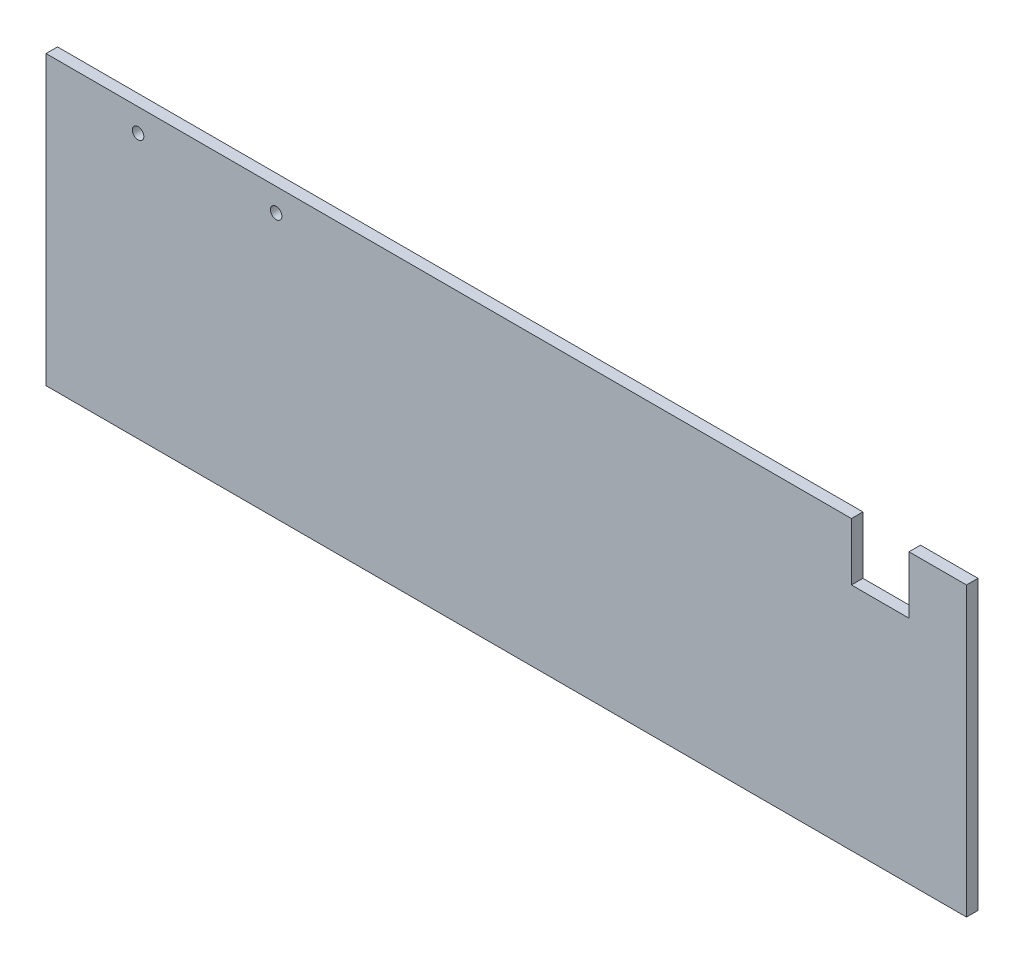
SolidWorks part; units mm, degrees
ref_plane "Front Plane" through (0, 0, 0) normal (0, 0, 1) x (1, 0, 0)
ref_plane "Top Plane" through (0, 0, 0) normal (0, 1, 0) x (1, 0, 0)
ref_plane "Right Plane" through (0, 0, 0) normal (1, 0, 0) x (0, 0, -1)
sketch "Sketch1" plane through (0, 0, 0) normal (0, 0, 1) x (1, 0, 0)
  line L0 (300, 125) -> (300, 75)
  line L1 (400, -125) -> (-400, -125)
  line L2 (400, -125) -> (400, 125)
  line L3 (400, 125) -> (350, 125)
  line L4 (-400, -125) -> (-400, 125)
  line L5 (400, -125) -> (-400, 125) construction
  line L6 (400, 125) -> (-400, -125) construction
  line L7 (300, 75) -> (350, 75)
  line L8 (350, 75) -> (350, 125)
  line L9 (300, 125) -> (-400, 125)
  point P0 (0, 0)
  dimension "D1" = 800
  dimension "D2" = 250
  dimension "D3" = 50
  dimension "D4" = 50
  dimension "D5" = 50
extrude "Boss-Extrude1" add sketch "Sketch1" along normal blind 10
sketch "Sketch3" plane through (0, 0, 10) normal (0, 0, 1) x (1, 0, 0)
  line L0 (-400, 125) -> (-400, -125) construction
  line L1 (300, 125) -> (-400, 125) construction
  circle A0 centre (-200, 105) radius 5
  circle A1 centre (-320, 105) radius 5
  dimension "D1" = 120
  dimension "D2" = 10
  dimension "D4" = 200
  dimension "D3" = 20
extrude "Cut-Extrude1" cut sketch "Sketch3" against normal up to next
